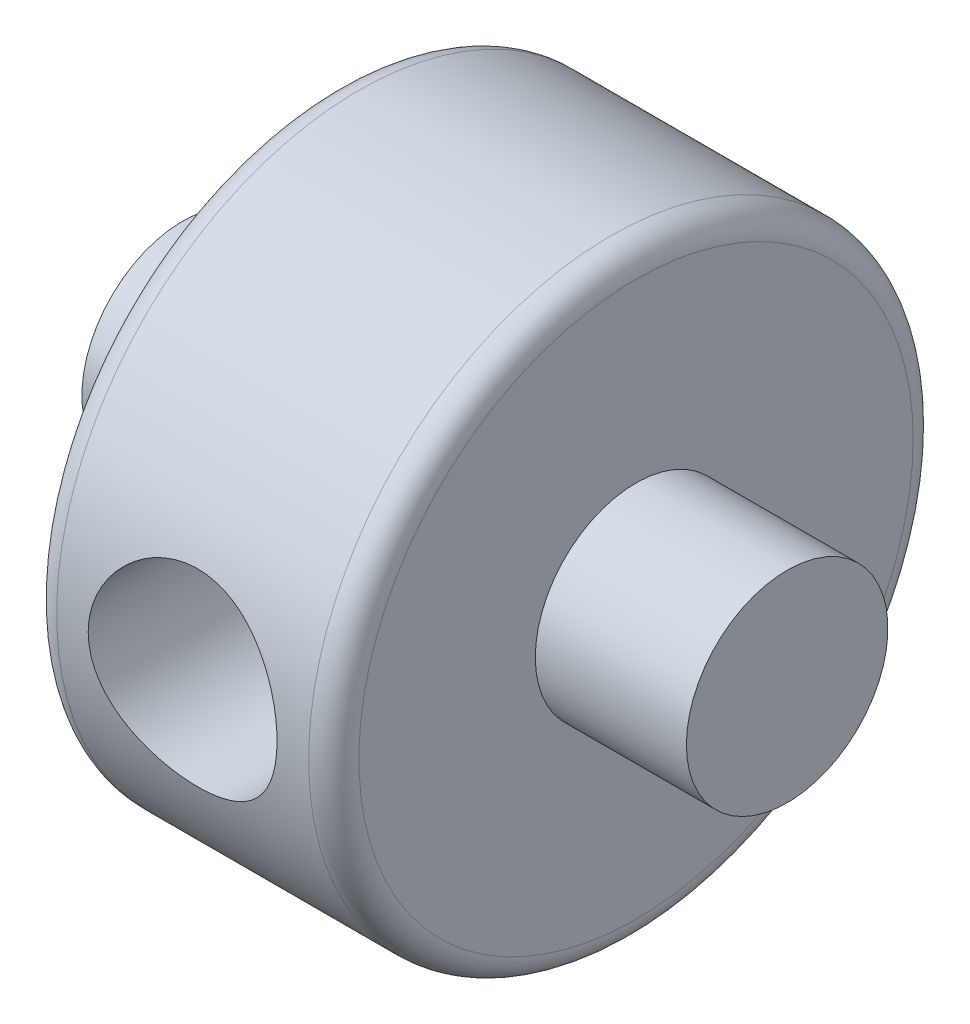
SolidWorks part; units mm, degrees
ref_plane "Front Plane" through (0, 0, 0) normal (0, 0, 1) x (1, 0, 0)
ref_plane "Top Plane" through (0, 0, 0) normal (0, 1, 0) x (1, 0, 0)
ref_plane "Right Plane" through (0, 0, 0) normal (1, 0, 0) x (0, 0, -1)
sketch "Sketch1" plane through (0, 0, 0) normal (1, 0, 0) x (0, 0, -1)
  circle A0 centre (0, 0) radius 9.525
  dimension "D1" = 19.05
extrude "Boss-Extrude1" add sketch "Sketch1" along normal mid plane 9.525
sketch "Sketch2" plane through (4.7625, 0, 0) normal (1, 0, 0) x (0, 0, -1)
  circle A0 centre (0, 0) radius 3.175
  dimension "D1" = 6.35
extrude "Boss-Extrude2" add sketch "Sketch2" along normal blind 4.7625
sketch "Sketch3" plane through (-4.7625, 0, 0) normal (-1, 0, 0) x (0, 0, 1)
  circle A0 centre (0, 0) radius 3.175
  dimension "D1" = 6.35
fillet "Fillet1" radius 0.7925 2 edges at (-4.7625, 0, -9.525) (4.7625, 0, -9.525)
ref_plane "Plane3" through (0, 0, 9.525) normal (0, 0, 1) x (1, 0, 0)
extrude "Boss-Extrude3" add sketch "Sketch3" along normal blind 4.7625
sketch "Sketch13" plane through (0, 0, 0) normal (0, 0, 1) x (1, 0, 0)
  circle A0 centre (0, 0) radius 2.9756
  dimension "D1" = 5.9512
extrude "Cut-Extrude1" cut sketch "Sketch13" along normal through all contours A0
